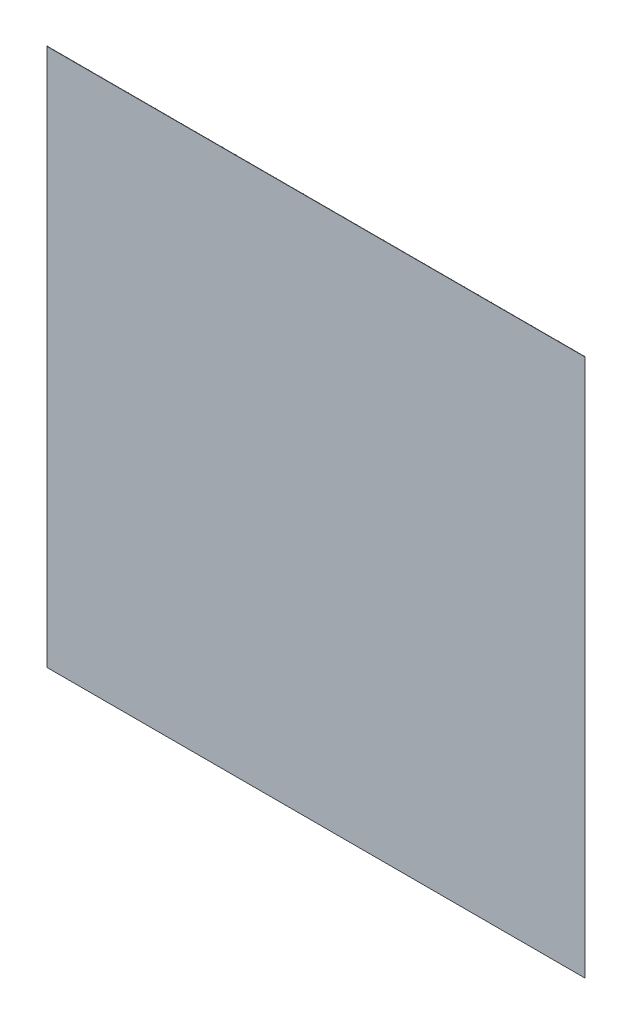
SolidWorks part; units mm, degrees
ref_plane "前视基准面" through (0, 0, 0) normal (0, 0, 1) x (1, 0, 0)
ref_plane "上视基准面" through (0, 0, 0) normal (0, 1, 0) x (1, 0, 0)
ref_plane "右视基准面" through (0, 0, 0) normal (1, 0, 0) x (0, 0, -1)
sketch "草图1" plane through (0, 0, 0) normal (0, 1, 0) x (1, 0, 0)
  line L0 (0, 0) -> (10, 0)
  line L1 (10, 0) -> (10, -5)
  line L2 (10, -5) -> (250, -5)
  line L3 (250, -5) -> (250, 0)
  line L4 (250, 0) -> (260, 0)
  line L5 (260, 0) -> (260, -5)
  line L6 (260, -5) -> (500, -5)
  line L7 (500, -5) -> (500, 0)
  line L8 (500, 0) -> (510, 0)
  line L9 (510, 0) -> (510, -5)
  line L10 (510, -5) -> (750, -5)
  line L11 (750, -5) -> (750, 0)
  line L12 (750, 0) -> (760, 0)
  line L13 (760, 0) -> (760, -5)
  line L14 (760, -5) -> (1000, -5)
  line L15 (1000, -5) -> (1000, 0)
  line L16 (1000, 0) -> (1010, 0)
  line L17 (1010, 0) -> (1010, -5)
  line L18 (1010, -5) -> (1250, -5)
  line L19 (1250, -5) -> (1250, 0)
  line L20 (1250, 0) -> (1260, 0)
  line L21 (1260, 0) -> (1260, -5)
  line L22 (1260, -5) -> (1500, -5)
  line L23 (1500, -5) -> (1500, 0)
  line L24 (1500, 0) -> (1510, 0)
  line L25 (1510, 0) -> (1510, -5)
  line L26 (1510, -5) -> (1750, -5)
  line L27 (1750, -5) -> (1750, 0)
  line L28 (1750, 0) -> (1760, 0)
  line L29 (1760, 0) -> (1760, -5)
  line L30 (1760, -5) -> (2000, -5)
  line L31 (2000, -5) -> (2000, 0)
  line L32 (2000, 0) -> (2010, 0)
  line L33 (2010, 0) -> (2010, -5)
  line L34 (2010, -5) -> (2250, -5)
  line L35 (2250, -5) -> (2250, 0)
  line L36 (2250, 0) -> (2260, 0)
  line L37 (2260, 0) -> (2260, -5)
  line L38 (2260, -5) -> (2500, -5)
  line L39 (2500, -5) -> (2500, 0)
  line L40 (2500, 0) -> (2510, 0)
  line L41 (2510, 0) -> (2510, -5)
  line L42 (2510, -5) -> (2750, -5)
  line L43 (2750, -5) -> (2750, 0)
  line L44 (2750, 0) -> (2760, 0)
  line L45 (2760, 0) -> (2760, -5)
  line L46 (2760, -5) -> (3000, -5)
  line L47 (3000, -5) -> (3000, 0)
  line L48 (3000, 0) -> (3010, 0)
  line L49 (3010, 0) -> (3010, -5)
  line L50 (3010, -5) -> (3250, -5)
  line L51 (3250, -5) -> (3250, 0)
  line L52 (3250, 0) -> (3260, 0)
  line L53 (3260, 0) -> (3260, -5)
  line L54 (3260, -5) -> (3500, -5)
  line L55 (3500, -5) -> (3500, 0)
  line L56 (3500, 0) -> (3510, 0)
  line L57 (3510, 0) -> (3510, -5)
  line L58 (3510, -5) -> (3750, -5)
  line L59 (3750, -5) -> (3750, 0)
  line L60 (3750, 0) -> (3760, 0)
  line L61 (3760, 0) -> (3760, -5)
  line L62 (3760, -5) -> (4000, -5)
  line L63 (4000, -5) -> (4000, 0)
  line L64 (4000, 0) -> (4010, 0)
  line L65 (4010, 0) -> (4010, -5)
  line L66 (4010, -5) -> (4250, -5)
  line L67 (4250, -5) -> (4250, 0)
  line L68 (4250, 0) -> (4260, 0)
  line L69 (4260, 0) -> (4260, -5)
  line L70 (4260, -5) -> (4500, -5)
  line L71 (4500, -5) -> (4500, 0)
  line L72 (4500, 0) -> (4510, 0)
  line L73 (4510, 0) -> (4510, -5)
  line L74 (4510, -5) -> (4750, -5)
  line L75 (4750, -5) -> (4750, 0)
  line L76 (4750, 0) -> (4760, 0)
  line L77 (4760, 0) -> (4760, -5)
  line L78 (4760, -5) -> (5000, -5)
  line L79 (5000, -5) -> (5000, 0)
  line L80 (5000, 0) -> (5010, 0)
  line L81 (5010, 0) -> (5010, -5)
  line L82 (5010, -5) -> (5250, -5)
  line L83 (5250, -5) -> (5250, 0)
  line L84 (5250, 0) -> (5260, 0)
  line L85 (5260, 0) -> (5260, -5)
  line L86 (5260, -5) -> (5500, -5)
  line L87 (5500, -5) -> (5500, 0)
  line L88 (5500, 0) -> (5510, 0)
  line L89 (5510, 0) -> (5510, -5)
  line L90 (5510, -5) -> (5750, -5)
  line L91 (5750, -5) -> (5750, 0)
  line L92 (5750, 0) -> (5760, 0)
  line L93 (5760, 0) -> (5760, -5)
  line L94 (5760, -5) -> (6000, -5)
  line L95 (6000, -5) -> (6000, 0)
  line L96 (6000, 0) -> (6010, 0)
  line L97 (6010, 0) -> (6010, -5)
  line L98 (6010, -5) -> (6250, -5)
  line L99 (6250, -5) -> (6250, 0)
  line L100 (6250, 0) -> (6260, 0)
  line L101 (6260, 0) -> (6260, -5)
  line L102 (6260, -5) -> (6500, -5)
  line L103 (6500, -5) -> (6500, 0)
  line L104 (6500, 0) -> (6510, 0)
  line L105 (6510, 0) -> (6510, -5)
  line L106 (6510, -5) -> (6750, -5)
  line L107 (6750, -5) -> (6750, 0)
  line L108 (6750, 0) -> (6760, 0)
  line L109 (6760, 0) -> (6760, -5)
  line L110 (6760, -5) -> (7000, -5)
  line L111 (7000, -5) -> (7000, 0)
  line L112 (7000, 0) -> (7010, 0)
  line L113 (7010, 0) -> (7010, -5)
  line L114 (7010, -5) -> (7250, -5)
  line L115 (7250, -5) -> (7250, 0)
  line L116 (7250, 0) -> (7260, 0)
  line L117 (7260, 0) -> (7260, -5)
  line L118 (7260, -5) -> (7500, -5)
  line L119 (7500, -5) -> (7500, 0)
  line L120 (7500, 0) -> (7510, 0)
  line L121 (7510, 0) -> (7510, -5)
  line L122 (7510, -5) -> (7750, -5)
  line L123 (7750, -5) -> (7750, 0)
  line L124 (7750, 0) -> (7760, 0)
  line L125 (7760, 0) -> (7760, -5)
  line L126 (7760, -5) -> (8000, -5)
  line L127 (8000, -5) -> (8000, 0)
  line L128 (8000, 0) -> (8010, 0)
  line L129 (8010, 0) -> (8010, -5)
  line L130 (8010, -5) -> (8250, -5)
  line L131 (8250, -5) -> (8250, 0)
  line L132 (8250, 0) -> (8260, 0)
  line L133 (8260, 0) -> (8260, -5)
  line L134 (8260, -5) -> (8500, -5)
  line L135 (8500, -5) -> (8500, 0)
  line L136 (8500, 0) -> (8510, 0)
  line L137 (8510, 0) -> (8510, -5)
  line L138 (8510, -5) -> (8750, -5)
  line L139 (8750, -5) -> (8750, 0)
  line L140 (8750, 0) -> (8760, 0)
  line L141 (8760, 0) -> (8760, -5)
  line L142 (8760, -5) -> (9000, -5)
  line L143 (9000, -5) -> (9000, 0)
  line L144 (9000, 0) -> (9010, 0)
  line L145 (9010, 0) -> (9010, -5)
  line L146 (9010, -5) -> (9250, -5)
  line L147 (9250, -5) -> (9250, 0)
  line L148 (9250, 0) -> (9260, 0)
  line L149 (9260, 0) -> (9260, -5)
  line L150 (9260, -5) -> (9500, -5)
  line L151 (9500, -5) -> (9500, 0)
  line L152 (9500, 0) -> (9510, 0)
  line L153 (9510, 0) -> (9510, -5)
  line L154 (9510, -5) -> (9750, -5)
  line L155 (9750, -5) -> (9750, 0)
  line L156 (9750, 0) -> (9760, 0)
  line L157 (9760, 0) -> (9760, -5)
  line L158 (9760, -5) -> (10000, -5)
  line L160 (0, 0) -> (0, -10)
  line L161 (0, -10) -> (10000, -10)
  line L162 (10000, -5) -> (10000, -10)
  line L164 (10000, -5) -> (10000, 0) [skipped]
  dimension "D1" = 40
extrude "凸台-拉伸1" add sketch "草图1" along normal blind 10000
